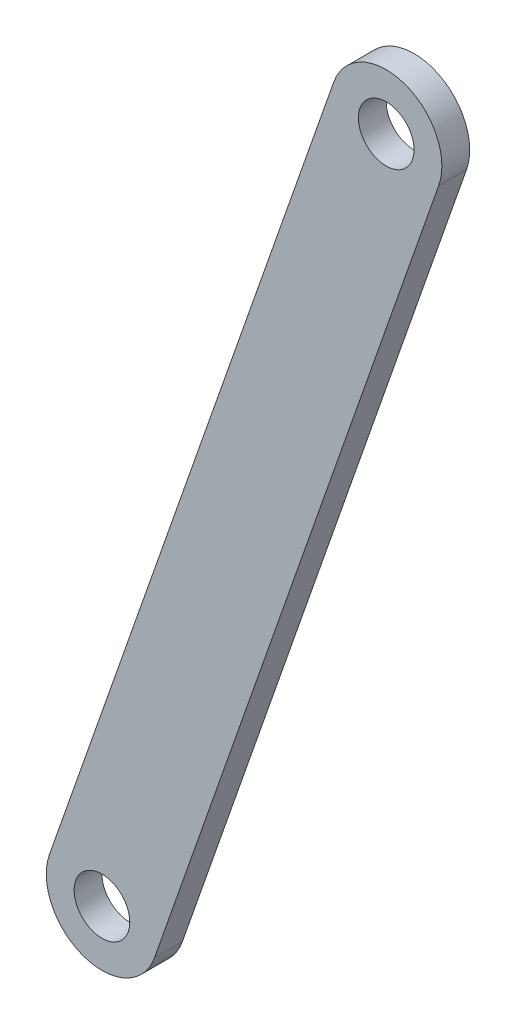
SolidWorks part; units mm, degrees
ref_plane "Front" through (0, 0, 0) normal (0, 0, 1) x (1, 0, 0)
ref_plane "Top" through (0, 0, 0) normal (0, 1, 0) x (1, 0, 0)
ref_plane "Right" through (0, 0, 0) normal (1, 0, 0) x (0, 0, -1)
sketch "Sketch1" plane through (0, 0, 0) normal (0, 0, 1) x (1, 0, 0)
  line L0 (-26.9521, -45.5152) -> (-43.1601, -91.7569) construction
  line L1 (-23.9558, -46.5654) -> (-40.1638, -92.8071)
  line L2 (-29.9484, -44.465) -> (-46.1564, -90.7067)
  arc A0 (-23.9558, -46.5654) -> (-29.9484, -44.465) centre (-26.9521, -45.5152) ccw
  arc A1 (-46.1564, -90.7067) -> (-40.1638, -92.8071) centre (-43.1601, -91.7569) ccw
  circle A2 centre (-43.1601, -91.7569) radius 1.5875
  circle A3 centre (-26.9521, -45.5152) radius 1.5875
  point P4 (-35.0561, -68.6361)
  dimension "D1" = 3.175
  dimension "D2" = 6.35
extrude "Boss-Extrude1" add sketch "Sketch1" against normal blind 1.5875 from offset 1.5875 offset against normal yes
